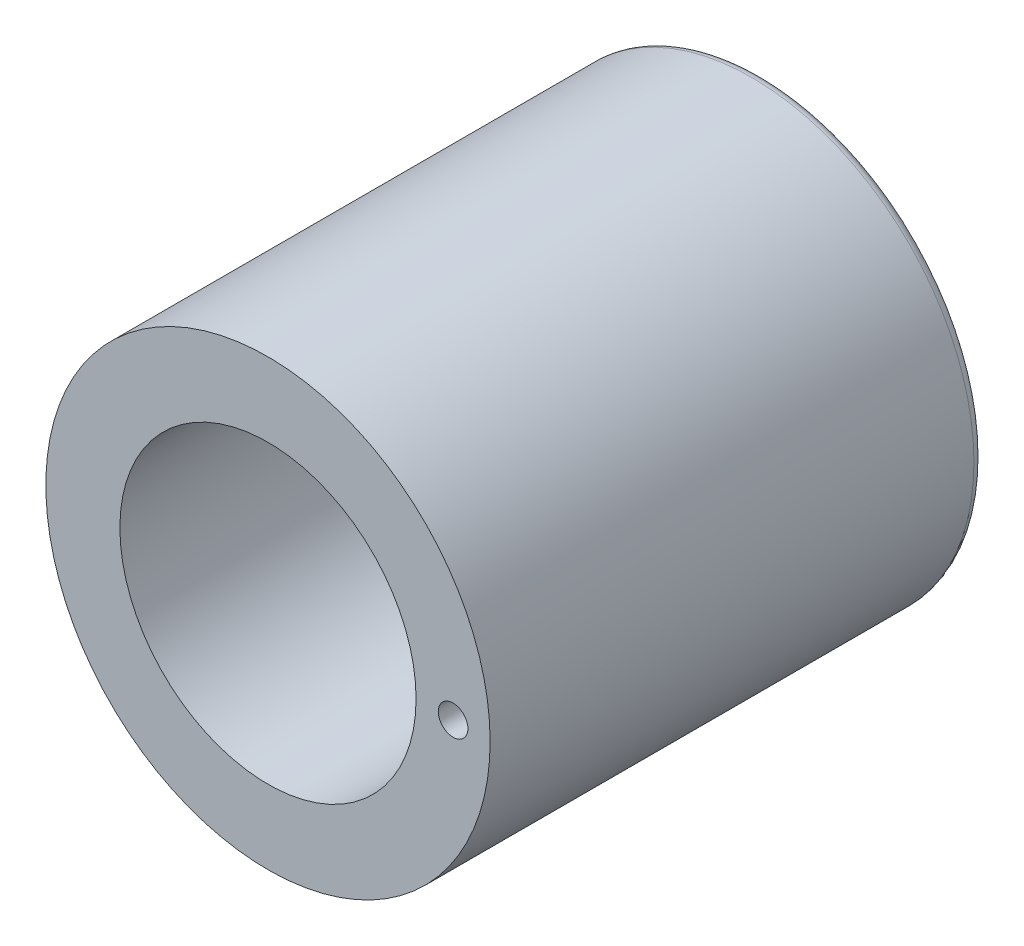
SolidWorks part; units mm, degrees
material "PW80:Mi:0:32:C1:0:1:2:Re:8:"
ref_plane "Plan1" through (0, 0, 0) normal (0, 0, 1) x (1, 0, 0)
ref_plane "Plan2" through (0, 0, 0) normal (0, 1, 0) x (1, 0, 0)
ref_plane "Plan3" through (0, 0, 0) normal (1, 0, 0) x (0, 0, -1)
sketch "Esquisse1" plane through (0, 0, 0) normal (0, 0, 1) x (1, 0, 0)
  circle A0 centre (0, 0) radius 45
extrude "Base-Extrusion" add sketch "Esquisse1" along normal blind 100
sketch "Esquisse2" plane through (0, 0, 100) normal (0, 0, 1) x (1, 0, 0)
  circle A0 centre (0, 0) radius 30
extrude "Enlèv. mat.-Extru.1" cut sketch "Esquisse2" against normal blind 100
sketch "Esquisse3" plane through (0, 0, 100) normal (0, 0, 1) x (1, 0, 0)
  circle A0 centre (37.5, 0) radius 3
extrude "Enlèv. mat.-Extru.2" cut sketch "Esquisse3" against normal blind 30
fillet "Congé1" radius 2
